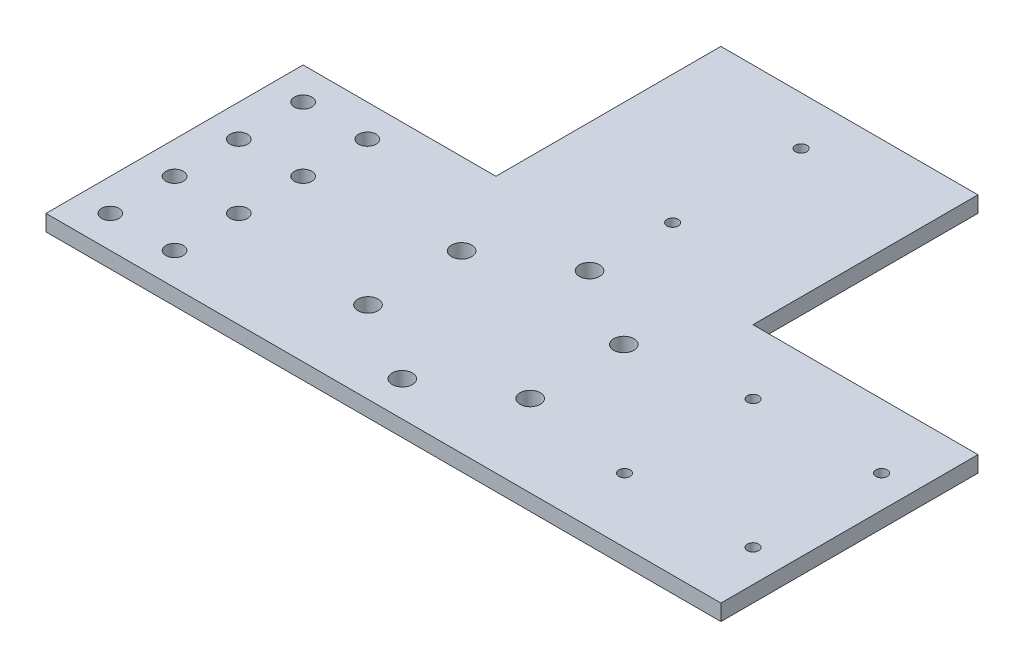
SolidWorks part; units mm, degrees
ref_plane "Front Plane" through (0, 0, 0) normal (0, 0, 1) x (1, 0, 0)
ref_plane "Top Plane" through (0, 0, 0) normal (0, 1, 0) x (1, 0, 0)
ref_plane "Right Plane" through (0, 0, 0) normal (1, 0, 0) x (0, 0, -1)
sketch "Sketch1" plane through (0, 0, 0) normal (0, 1, 0) x (1, 0, 0)
  line L0 (6.35, -31.75) -> (6.35, 63.5)
  line L1 (-31.75, -31.75) -> (95.25, -31.75)
  line L2 (-31.75, -31.75) -> (-31.75, 19.05)
  line L3 (-31.75, 19.05) -> (95.25, 19.05)
  line L4 (95.25, -31.75) -> (95.25, 19.05)
  line L5 (6.35, -31.75) -> (57.15, -31.75)
  line L6 (6.35, 63.5) -> (57.15, 63.5)
  line L7 (57.15, -31.75) -> (57.15, 63.5)
  line L8 (6.35, -31.75) -> (57.15, 63.5) construction
  line L9 (6.35, 63.5) -> (57.15, -31.75) construction
  line L11 (95.25, 19.05) -> (101.6156, 19.05)
  line L12 (95.25, 19.05) -> (95.25, -31.75)
  line L13 (95.25, -31.75) -> (101.6156, -31.75)
  line L14 (101.6156, 19.05) -> (101.6156, -31.75)
  circle A0 centre (31.75, -6.35) radius 18.542
  point P5 (31.75, -31.75)
  point P6 (31.75, -6.35)
  point P7 (31.75, 15.875)
  dimension "D9" = 37.084
  dimension "D1" = 127
  dimension "D2" = 50.8
  dimension "D3" = 50.8
  dimension "D4" = 25.4
  dimension "D5" = 95.25
  dimension "D6" = 0
  dimension "D7" = 25.4
  dimension "D8" = 25.4
extrude "Boss-Extrude1" add sketch "Sketch1" along normal blind 3.175 contours L4 L3 L2 L1 | L0 L5 L7 L6 | L12 L11 L14 L13
sketch "Sketch8" plane through (0, 3.175, 0) normal (0, 1, 0) x (1, 0, 0)
  line L0 (-31.75, -31.75) -> (-31.75, 19.05) construction
  line L1 (-31.75, 19.05) -> (6.35, 19.05) construction
  point P0 (-25.4, 12.7)
  point P5 (0, 0)
  point P8 (-12.7, 12.7)
  point P9 (-12.7, 0)
  point P10 (-12.7, -12.7)
  point P11 (-12.7, -25.4)
  point P12 (-25.4, 0)
  point P13 (-25.4, -12.7)
  point P14 (-25.4, -25.4)
  dimension "D1" = 6.35
  dimension "D2" = 6.35
  dimension "D3" = 2
  dimension "D4" = 4
hole_wizard "Tap Drill for #8-32 Tap1" positions "3DSketch8" profile "Sketch14" hole size "#8-32" standard "ANSI Inch" end condition through all
sketch3d "3DSketch8"
  point P0 (-12.7, 3.175, 0)
  point P2 (-12.7, 3.175, 0)
  point P4 (-12.7, 3.175, 0)
  point P12 (-25.4, 3.175, 0)
  point P15 (-25.4, 3.175, 12.7)
  point P18 (-25.4, 3.175, 25.4)
  point P21 (-12.7, 3.175, 25.4)
  point P24 (-12.7, 3.175, -12.7)
  point P27 (-25.4, 3.175, -12.7)
  point P52 (-12.7, 3.175, 12.7)
sketch "Sketch14" plane through (-12.7, 3.175, 0) normal (1, 0, 0) x (0, 0, 1)
  line L0 (0, 0) -> (0, 3.175)
  line L1 (0, 3.175) -> (1.7272, 3.175)
  line L2 (1.7272, 3.175) -> (1.7272, 0)
  line L5 (1.7272, 0) -> (0, 0)
  line L11 (0, -6.35) -> (0, 107.95) construction
  dimension "Thru Hole Dia." = 3.4544
  dimension "Thru Hole Depth" = 3.175
sketch "Sketch15" plane through (0, 3.175, 0) normal (0, 1, 0) x (1, 0, 0)
  line L0 (57.15, 19.05) -> (57.15, -31.75)
  line L1 (-31.75, -31.75) -> (101.6156, -31.75) construction
  line L2 (69.8656, -19.05) -> (95.2656, -19.05)
  line L3 (69.8656, -19.05) -> (69.8656, 6.35)
  line L4 (95.2656, -19.05) -> (95.2656, 6.35)
  line L5 (69.8656, 6.35) -> (95.2656, 6.35)
  line L6 (101.6156, 19.05) -> (101.6156, -31.75) construction
  circle A0 centre (69.8656, 6.35) radius 1.524
  circle A1 centre (95.2656, 6.35) radius 1.524
  circle A2 centre (69.8656, -19.05) radius 1.524
  circle A3 centre (95.2656, -19.05) radius 1.524
  point P13 (95.2656, 6.35)
  point P14 (95.2656, -19.05)
  point P15 (69.8656, -19.05)
  dimension "D5" = 3.048
  dimension "D1" = 25.4
  dimension "D2" = 25.4
  dimension "D3" = 6.35
  dimension "D4" = 12.7
  dimension "D6" = 2
  dimension "D7" = 2
sketch "Sketch17" plane through (0, 3.175, 0) normal (0, 1, 0) x (1, 0, 0)
  line L0 (-31.75, -31.75) -> (101.6156, -31.75) construction
  line L1 (31.75, -6.35) -> (31.75, 12.15) construction
  line L2 (-31.75, -31.75) -> (-31.75, 19.05) construction
  line L3 (47.7715, 2.9) -> (31.75, -6.35) construction
  line L4 (31.75, -6.35) -> (50.25, -6.35) construction
  circle A0 centre (31.75, -6.35) radius 18.5
  point P0 (31.75, -6.35)
  point P7 (31.75, 12.15)
  point P10 (47.7715, 2.9)
  point P11 (47.7715, -15.6)
  point P12 (31.75, -24.85)
  point P13 (15.7285, -15.6)
  point P14 (15.7285, 2.9)
  point P15 (31.75, -6.35)
  point P17 (43.1215, 0)
  dimension "D3" = 30
  dimension "D4" = 37
  dimension "D1" = 25.4
  dimension "D2" = 63.5
hole_wizard "Ø4.0 (4) Diameter Hole1" positions "3DSketch9" profile "Sketch18" hole size "Ø4.0" standard "ANSI Metric" end condition through all
sketch3d "3DSketch9"
  point P0 (31.75, 3.175, -12.15)
  point P3 (47.7715, 3.175, -2.9)
  point P6 (47.7715, 3.175, 15.6)
  point P9 (31.75, 3.175, 24.85)
  point P12 (15.7285, 3.175, 15.6)
  point P15 (15.7285, 3.175, -2.9)
sketch "Sketch18" plane through (31.75, 3.175, -12.15) normal (1, 0, 0) x (0, 0, 1)
  line L0 (0, 0) -> (0, 3.175)
  line L1 (0, 3.175) -> (2, 3.175)
  line L2 (2, 3.175) -> (2, 0)
  line L5 (2, 0) -> (0, 0)
  line L11 (0, -6.35) -> (0, 107.95) construction
  dimension "Thru Hole Dia." = 4
  dimension "Thru Hole Depth" = 3.175
sketch "Sketch19" plane through (0, 3.175, 0) normal (0, 1, 0) x (1, 0, 0)
  line L0 (31.75, 12.15) -> (31.75, 63.5)
  line L1 (6.35, 63.5) -> (57.15, 63.5) construction
  line L2 (57.15, 19.05) -> (101.6156, 19.05) construction
  circle A0 centre (31.75, 53.975) radius 1.6319
  circle A1 centre (31.75, 28.575) radius 1.6319
  point P5 (31.75, 57.15)
  point P6 (31.75, 25.4)
  point P9 (31.75, 53.975)
  point P10 (31.75, 28.575)
  dimension "D1" = 6.35
  dimension "D2" = 6.35
  dimension "D3" = 3.175
  dimension "D4" = 25.4
hole_wizard "Tap Drill for #4-40 Tap1" positions "3DSketch10" profile "Sketch20" hole size "#4-40" standard "ANSI Inch" end condition through all
sketch3d "3DSketch10"
  point P0 (69.8656, 3.175, -6.35)
  point P3 (95.2656, 3.175, -6.35)
  point P6 (95.2656, 3.175, 19.05)
  point P9 (69.8656, 3.175, 19.05)
sketch "Sketch20" plane through (69.8656, 3.175, -6.35) normal (1, 0, 0) x (0, 0, 1)
  line L0 (0, 0) -> (0, 3.175)
  line L1 (0, 3.175) -> (1.1303, 3.175)
  line L2 (1.1303, 3.175) -> (1.1303, 0)
  line L5 (1.1303, 0) -> (0, 0)
  line L11 (0, -6.35) -> (0, 107.95) construction
  dimension "Thru Hole Dia." = 2.2606
  dimension "Thru Hole Depth" = 3.175
hole_wizard "Tap Drill for #4-40 Tap2" positions "3DSketch11" profile "Sketch21" hole size "#4-40" standard "ANSI Inch" end condition through all
sketch3d "3DSketch11"
  point P0 (31.75, 3.175, -53.975)
  point P3 (31.75, 3.175, -28.575)
sketch "Sketch21" plane through (31.75, 3.175, -53.975) normal (1, 0, 0) x (0, 0, 1)
  line L0 (0, 0) -> (0, 3.175)
  line L1 (0, 3.175) -> (1.1303, 3.175)
  line L2 (1.1303, 3.175) -> (1.1303, 0)
  line L5 (1.1303, 0) -> (0, 0)
  line L11 (0, -6.35) -> (0, 107.95) construction
  dimension "Thru Hole Dia." = 2.2606
  dimension "Thru Hole Depth" = 3.175
